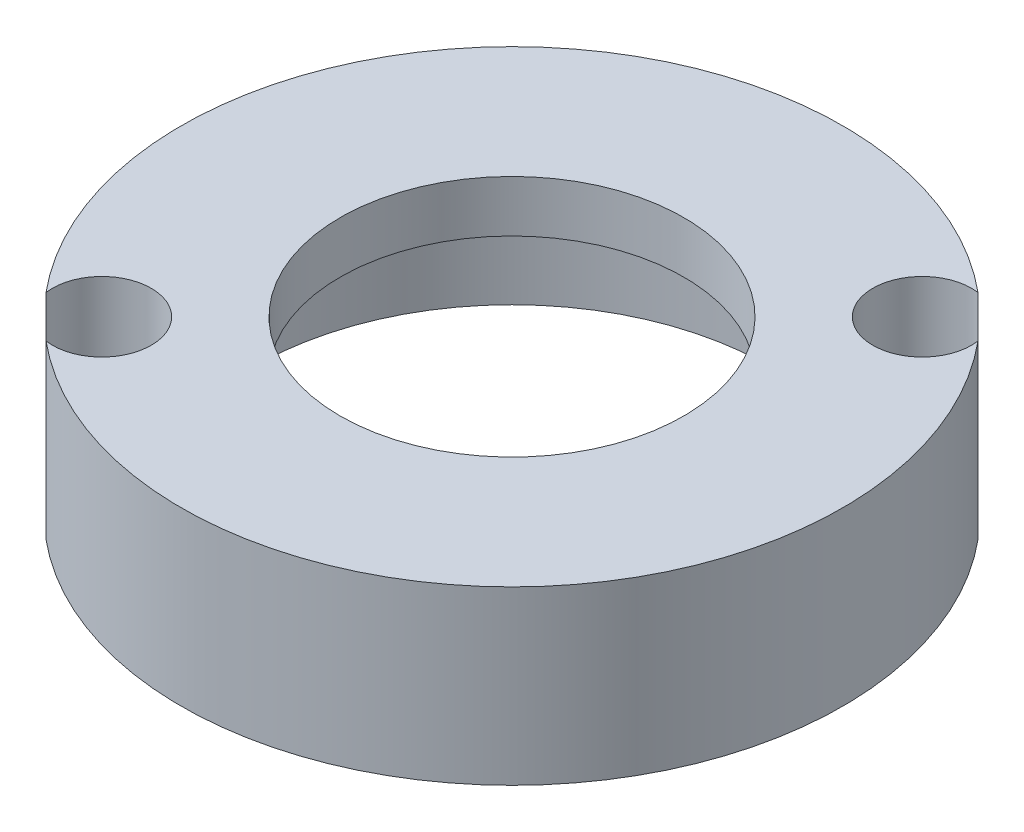
SolidWorks part; units mm, degrees
ref_plane "Front Plane" through (0, 0, 0) normal (0, 0, 1) x (1, 0, 0)
ref_plane "Top Plane" through (0, 0, 0) normal (0, 1, 0) x (1, 0, 0)
ref_plane "Right Plane" through (0, 0, 0) normal (1, 0, 0) x (0, 0, -1)
sketch "Sketch1" plane through (0, 0, 0) normal (0, 1, 0) x (1, 0, 0)
  circle A0 centre (0, 0) radius 7.7
  circle A1 centre (0, 0) radius 4
  dimension "D1" = 15.4
  dimension "D2" = 8
extrude "Boss-Extrude1" add sketch "Sketch1" along normal blind 4
sketch "Sketch2" plane through (0, 0, 0) normal (0, -1, 0) x (1, 0, 0)
  circle A0 centre (0, 0) radius 6
  dimension "D1" = 12
extrude "Cut-Extrude1" cut sketch "Sketch2" against normal offset from surface (2.8 mm away) 1.2 up to face at (0, 4, 7.7)
sketch "Sketch3" plane through (0, 4, 0) normal (0, 1, 0) x (1, 0, 0)
  line L0 (-4.773, -4.773) -> (4.773, 4.773) construction
  line L1 (0, 0) -> (3.0235, 0) construction
  circle A0 centre (4.773, 4.773) radius 1.15
  circle A1 centre (-4.773, -4.773) radius 1.15
  point P4 (0, 0)
  dimension "D3" = 2.3
  dimension "D1" = 45
  dimension "D2" = 13.5
extrude "Cut-Extrude2" cut sketch "Sketch3" against normal through all
